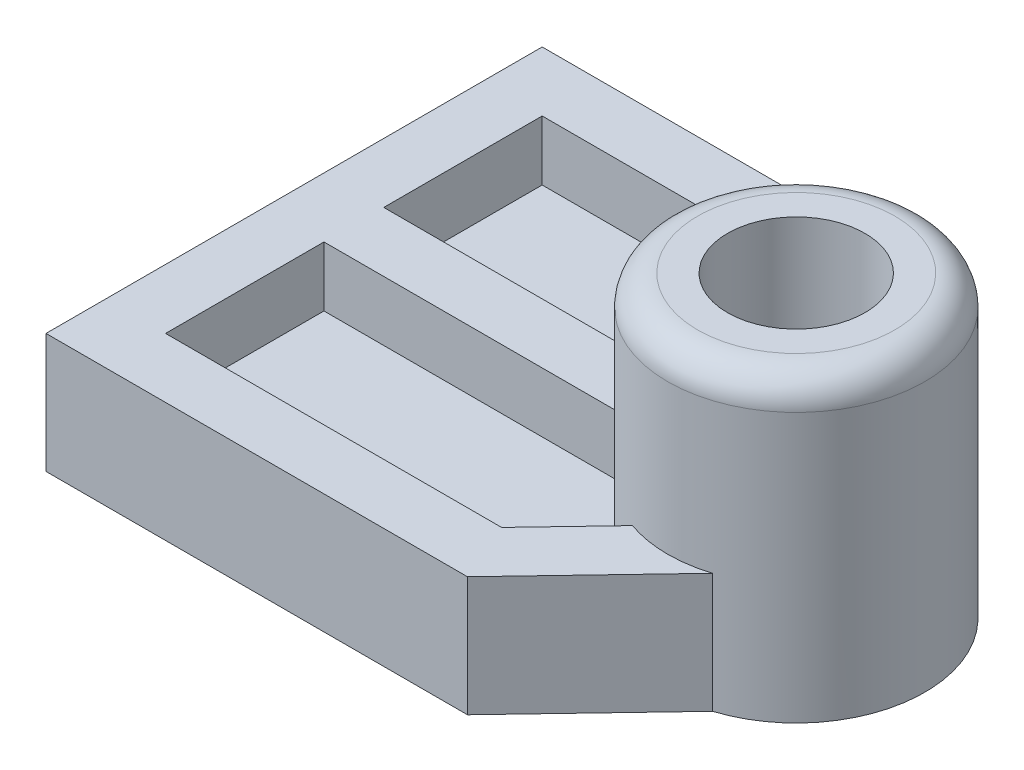
SolidWorks part; units mm, degrees
ref_plane "Front Plane" through (0, 0, 0) normal (0, 0, 1) x (1, 0, 0)
ref_plane "Top Plane" through (0, 0, 0) normal (0, 1, 0) x (1, 0, 0)
ref_plane "Right Plane" through (0, 0, 0) normal (1, 0, 0) x (0, 0, -1)
sketch "Sketch1" plane through (0, 0, 0) normal (0, 1, 0) x (1, 0, 0)
  line L1 (-5.25, 4.15) -> (5.25, 4.15)
  line L2 (-5.25, 4.15) -> (-5.25, -4.15)
  line L3 (-5.25, -4.15) -> (5.25, -4.15)
  line L4 (5.25, 4.15) -> (5.25, -4.15)
  line L5 (-5.25, 4.15) -> (5.25, -4.15) construction
  line L6 (-5.25, -4.15) -> (5.25, 4.15) construction
  point P0 (0, 0)
  dimension "D1" = 5.25
  dimension "D2" = 4.15
extrude "Boss-Extrude1" add sketch "Sketch1" along normal blind 5
sketch "Sketch2" plane through (0, 5, 0) normal (0, 1, 0) x (1, 0, 0)
  line L0 (-5.25, -4.15) -> (1.75, -4.15)
  line L1 (-5.25, -4.15) -> (5.25, -4.15) construction
  line L2 (1.75, -4.15) -> (3.75, -2.0494)
  line L4 (5.25, -4.15) -> (3.75, -4.15)
  line L5 (5.25, -4.15) -> (5.25, 4.15) construction
  line L6 (1.75, 4.15) -> (3.75, 2.0494)
  line L7 (5.25, 4.15) -> (-5.25, 4.15) construction
  circle A0 centre (3.1, 0) radius 2.15
  line M4 (5.25, -4.15) -> (5.25, 4.15)
  line M5 (5.25, 4.15) -> (-5.25, 4.15)
  line M7 (-5.25, -4.15) -> (5.25, -4.15)
  dimension "D1" = 2.15
extrude "Cut-Extrude1" cut sketch "Sketch2" against normal blind 10 contours A0 L6 M4 M5 | A0 L2 M7 M4
sketch "Sketch3" plane through (-5.25, 0, 0) normal (-1, 0, 0) x (0, 0, 1)
  line L1 (-4.15, 0) -> (4.15, 0)
  line L2 (-4.15, 0) -> (-4.15, 5)
  line L3 (-4.15, 5) -> (4.15, 5)
  line L4 (4.15, 0) -> (4.15, 5)
extrude "Boss-Extrude2" add sketch "Sketch3" along normal blind 0.05
sketch "Sketch4" plane through (0, 5, 0) normal (0, 1, 0) x (1, 0, 0)
  line L0 (3.75, 2.0494) -> (1.75, 4.15)
  line L1 (1.75, 4.15) -> (-5.3, 4.15)
  line L2 (-5.3, 4.15) -> (-5.3, -4.15)
  line L3 (-5.3, -4.15) -> (1.75, -4.15)
  line L4 (1.75, -4.15) -> (3.75, -2.0494)
  circle A0 centre (3.1, 0) radius 2.15
  arc A1 (3.75, -2.0494) -> (3.75, 2.0494) centre (3.1, 0) ccw construction
  point P5 (5.25, 0)
  line M2 (1.75, -4.15) -> (3.75, -2.0494)
  line M4 (3.75, 2.0494) -> (1.75, 4.15)
  line M5 (1.75, 4.15) -> (-5.3, 4.15)
  line M6 (-5.3, 4.15) -> (-5.3, -4.15)
  line M7 (-5.3, -4.15) -> (1.75, -4.15)
  dimension "D1" = 2.15
extrude "Cut-Extrude2" cut sketch "Sketch4" against normal blind 3 contours A0 M4 M5 M6 M7 M2
sketch "Sketch5" plane through (0, 5, 0) normal (0, 1, 0) x (1, 0, 0)
  circle A0 centre (3.1, 0) radius 1.15
  arc A1 (3.75, 2.0494) -> (3.75, -2.0494) centre (3.1, 0) ccw construction
  point P5 (0.95, 0)
  dimension "D1" = 2.15
extrude "Cut-Extrude3" cut sketch "Sketch5" against normal blind 5
sketch "Sketch6" plane through (0, 2, 0) normal (0, 1, 0) x (1, 0, 0)
  line L0 (-5.3, -4.15) -> (1.75, -4.15) construction
  line L1 (-5.3, 4.15) -> (-4.3, 4.15)
  line L2 (-5.3, 4.15) -> (-5.3, -4.15)
  line L3 (-5.3, -4.15) -> (-4.3, -4.15)
  line L4 (-4.3, 4.15) -> (-4.3, -4.15)
  line L5 (1.75, 4.15) -> (1.0429, 3.4429)
  line L6 (1.75, -4.15) -> (-5.3, -4.15)
  line L7 (1.75, -4.15) -> (1.75, -3.15)
  line L8 (1.75, -3.15) -> (-5.3, -3.15)
  line L9 (-5.3, -4.15) -> (-5.3, -3.15)
  line L10 (-5.3, 4.15) -> (1.75, 4.15)
  line L11 (-5.3, 4.15) -> (-5.3, 3.15)
  line L12 (-5.3, 3.15) -> (1.75, 3.15)
  line L13 (1.75, 4.15) -> (1.75, 3.15)
  line L14 (3.75, 2.0494) -> (3.0429, 1.3423)
  line L15 (1.0429, 3.4429) -> (3.0429, 1.3423)
  line L16 (3.75, 2.0494) -> (1.75, 4.15)
  line L17 (1.75, -4.15) -> (1.0429, -3.4429)
  line L18 (3.75, -2.0494) -> (3.0429, -1.3423)
  line L19 (1.0429, -3.4429) -> (3.0429, -1.3423)
  line L20 (3.75, -2.0494) -> (1.75, -4.15)
  line L21 (-5.3, 0.5) -> (-5.3, -0.5)
  line L22 (-5.3, -0.5) -> (-1.2124, -0.5)
  line L23 (-1.2124, -0.5) -> (-1.2124, 0.5)
  line L24 (-1.2124, 0.5) -> (-5.3, 0.5)
  line L25 (-1.2124, 0.5) -> (1.0089, 0.5)
  line L26 (-1.2124, -0.5) -> (1.0089, -0.5)
  arc A0 (3.75, 2.0494) -> (3.75, -2.0494) centre (3.1, 0) ccw construction
  circle A1 centre (3.1, 0) radius 2.15 construction
  circle A2 centre (3.1, 0) radius 2.15
  point P25 (-5.3, 0)
  point P36 (-1.2124, -1.9708)
  point P37 (0.95, 0)
  arc M22 (3.75, -2.0494) -> (3.75, 2.0494) centre (3.1, 0) cw
  dimension "D1" = 1
  dimension "D2" = 1
  dimension "D3" = 1
  dimension "D4" = 0.5
  dimension "D5" = 2.15
extrude "Cut-Extrude4" cut sketch "Sketch6" against normal blind 1 contours L24 L25 L15 L12 L4 M22 | L26 L22 L4 L8 L19 M22
fillet "Fillet1" radius 0.5 1 edges at (3.1, 5, 2.15)
